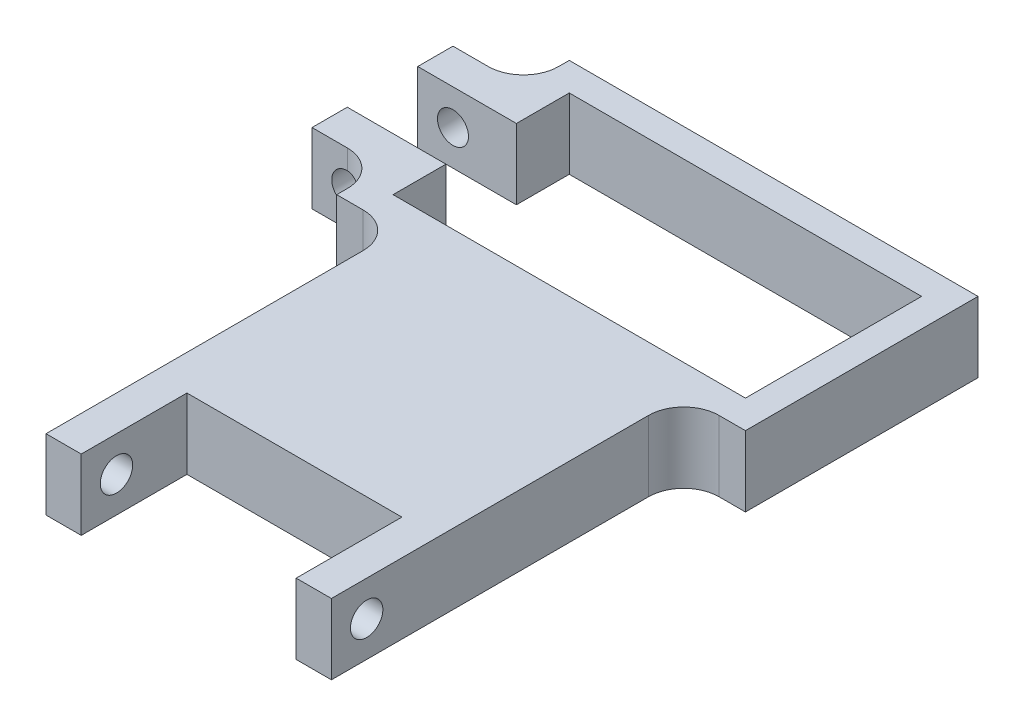
SolidWorks part; units mm, degrees
ref_plane "Alzado" through (0, 0, 0) normal (0, 0, 1) x (1, 0, 0)
ref_plane "Planta" through (0, 0, 0) normal (0, 1, 0) x (1, 0, 0)
ref_plane "Vista lateral" through (0, 0, 0) normal (1, 0, 0) x (0, 0, -1)
sketch "Croquis1" plane through (0, 0, 0) normal (0, 1, 0) x (1, 0, 0)
  line L0 (0, -66.5) -> (0, -51.5) construction
  line L1 (-25, -12.5) -> (25, -12.5)
  line L2 (-25, -12.5) -> (-25, 12.5)
  line L3 (-25, 12.5) -> (25, 12.5)
  line L4 (25, -12.5) -> (25, 12.5)
  line L5 (-25, -12.5) -> (25, 12.5) construction
  line L6 (-25, 12.5) -> (25, -12.5) construction
  line L7 (-29, -16.5) -> (29, -16.5)
  line L8 (-29, -16.5) -> (-29, 16.5)
  line L9 (-29, 16.5) -> (29, 16.5)
  line L10 (29, -16.5) -> (29, 16.5)
  line L11 (-29, -16.5) -> (29, 16.5) construction
  line L12 (-29, 16.5) -> (29, -16.5) construction
  line L13 (-29, -16.5) -> (29, -16.5)
  line L14 (-29, -16.5) -> (-29, -66.5)
  line L15 (-29, -66.5) -> (29, -66.5)
  line L16 (29, -16.5) -> (29, -66.5)
  line L17 (-15.25, -51.5) -> (15.25, -51.5)
  line L18 (-15.25, -51.5) -> (-15.25, -66.5)
  line L19 (15.25, -51.5) -> (15.25, -66.5)
  line L20 (-15.25, -59) -> (-20.25, -59) construction
  line L21 (15.25, -59) -> (20.25, -59) construction
  line L22 (-20.25, -66.5) -> (-20.25, -16.5)
  line L23 (20.25, -66.5) -> (20.25, -16.5)
  point P0 (0, 0)
  point P6 (0, 0)
  point P18 (0, -51.5)
extrude "Saliente-Extruir1" add sketch "Croquis1" along normal blind 10 contours L7 L13 L10 L9 L8 L4 L1 L2 L3 | L15 L23 L13 L22 L18 L17 L19
fillet "Redondeo1" radius 5 1 edges at (20.25, 5, 16.5)
fillet "Redondeo2" radius 5 1 edges at (-20.25, 5, 16.5)
sketch "Croquis2" plane through (-20.25, 0, 0) normal (-1, 0, 0) x (0, 0, 1)
  line L0 (66.5, 5) -> (61.5, 5) construction
  line L1 (66.5, 10) -> (66.5, 0) construction
  circle A0 centre (61.5, 5) radius 2.3
extrude "Cortar-Extruir1" cut sketch "Croquis2" against normal blind 52
sketch "Croquis3" plane through (0, 0, 0) normal (0, -1, 0) x (1, 0, 0)
  line L0 (-25, 0) -> (-29, 0) construction
  line L1 (-25, 12.5) -> (-25, -12.5) construction
  line L2 (-29, 16.5) -> (-29, -16.5) construction
  line L4 (-25, -5) -> (-29, -5)
  line L5 (-25, -5) -> (-25, 5)
  line L6 (-25, 5) -> (-29, 5)
  line L7 (-29, -5) -> (-29, 5)
  line L8 (-25, -5) -> (-29, 5) construction
  line L9 (-25, 5) -> (-29, -5) construction
  point P6 (-27, 0)
extrude "Cortar-Extruir2" cut sketch "Croquis3" against normal blind 20
sketch "Croquis4" plane through (-29, 0, 0) normal (-1, 0, 0) x (0, 0, 1)
  line L0 (-5, 0) -> (-16.5, 0) construction
  line L1 (-5, 10) -> (-10, 10)
  line L2 (-5, 10) -> (-5, 0)
  line L3 (-5, 0) -> (-10, 0)
  line L4 (-10, 10) -> (-10, 0)
  line L5 (16.5, 0) -> (5, 0) construction
  line L6 (5, 10) -> (10, 10)
  line L7 (5, 10) -> (5, 0)
  line L8 (5, 0) -> (10, 0)
  line L9 (10, 10) -> (10, 0)
extrude "Saliente-Extruir2" add sketch "Croquis4" along normal blind 10
fillet "Redondeo3" radius 5 1 edges at (-29, 5, -10)
fillet "Redondeo4" radius 5 1 edges at (-29, 5, 10)
sketch "Croquis5" plane through (0, 0, 10) normal (0, 0, 1) x (1, 0, 0)
  line L0 (-39, 5) -> (-34, 5) construction
  line L1 (-39, 0) -> (-39, 10) construction
  circle A0 centre (-34, 5) radius 2.2
extrude "Cortar-Extruir4" cut sketch "Croquis5" against normal blind 27 and the other way blind 27
